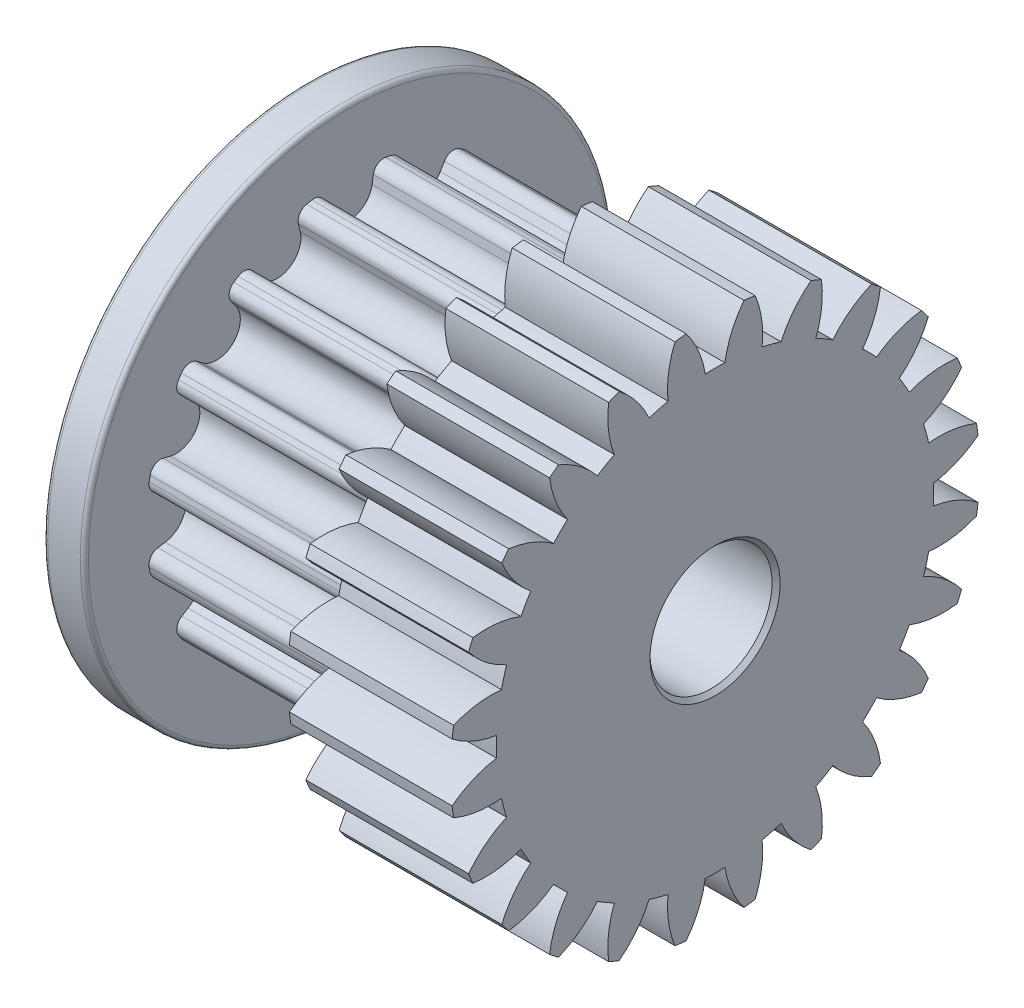
SolidWorks part; units mm, degrees
ref_plane "前视基准面" through (0, 0, 0) normal (0, 0, 1) x (1, 0, 0)
ref_plane "上视基准面" through (0, 0, 0) normal (0, 1, 0) x (1, 0, 0)
ref_plane "右视基准面" through (0, 0, 0) normal (1, 0, 0) x (0, 0, -1)
ref_plane "基准面4" through (0, 0, 0) normal (-1, 0, 0) x (0, -1, 0)
sketch "草图1" plane through (0, 0, 0) normal (-1, 0, 0) x (0, -1, 0)
  arc A0 (-0.7113, 6.461) -> (-0.9851, 6.4249) centre (0, 0) ccw
  arc A1 (-0.9851, 6.4249) -> (-1.1561, 5.2482) centre (1.2304, 5.5023) ccw
  arc A2 (-1.1561, 5.2482) -> (-1.6229, 5.1231) centre (0, 0) ccw
  arc A3 (-1.6229, 5.1231) -> (-2.3593, 6.0567) centre (-3.8167, 4.1499) ccw
  arc A4 (-2.3593, 6.0567) -> (-2.6144, 5.951) centre (0, 0) ccw
  arc A5 (-2.6144, 5.951) -> (-2.475, 4.7701) centre (-0.2356, 5.6332) ccw
  arc A6 (-2.475, 4.7701) -> (-2.8936, 4.5285) centre (0, 0) ccw
  arc A7 (-2.8936, 4.5285) -> (-3.8465, 5.2397) centre (-4.7607, 3.0206) ccw
  arc A8 (-3.8465, 5.2397) -> (-4.0656, 5.0716) centre (0, 0) ccw
  arc A9 (-4.0656, 5.0716) -> (-3.6253, 3.967) centre (-1.6855, 5.3803) ccw
  arc A10 (-3.6253, 3.967) -> (-3.967, 3.6253) centre (0, 0) ccw
  arc A11 (-3.967, 3.6253) -> (-5.0716, 4.0656) centre (-5.3803, 1.6855) ccw
  arc A12 (-5.0716, 4.0656) -> (-5.2397, 3.8465) centre (0, 0) ccw
  arc A13 (-5.2397, 3.8465) -> (-4.5285, 2.8936) centre (-3.0206, 4.7607) ccw
  arc A14 (-4.5285, 2.8936) -> (-4.7701, 2.475) centre (0, 0) ccw
  arc A15 (-4.7701, 2.475) -> (-5.951, 2.6144) centre (-5.6332, 0.2356) ccw
  arc A16 (-5.951, 2.6144) -> (-6.0567, 2.3593) centre (0, 0) ccw
  arc A17 (-6.0567, 2.3593) -> (-5.1231, 1.6229) centre (-4.1499, 3.8167) ccw
  arc A18 (-5.1231, 1.6229) -> (-5.2482, 1.1561) centre (0, 0) ccw
  arc A19 (-5.2482, 1.1561) -> (-6.4249, 0.9851) centre (-5.5023, -1.2304) ccw
  arc A20 (-6.4249, 0.9851) -> (-6.461, 0.7113) centre (0, 0) ccw
  arc A21 (-6.461, 0.7113) -> (-5.3686, 0.2416) centre (-4.9963, 2.6126) ccw
  arc A22 (-5.3686, 0.2416) -> (-5.3686, -0.2416) centre (0, 0) ccw
  arc A23 (-5.3686, -0.2416) -> (-6.461, -0.7113) centre (-4.9963, -2.6126) ccw
  arc A24 (-6.461, -0.7113) -> (-6.4249, -0.9851) centre (0, 0) ccw
  arc A25 (-6.4249, -0.9851) -> (-5.2482, -1.1561) centre (-5.5023, 1.2304) ccw
  arc A26 (-5.2482, -1.1561) -> (-5.1231, -1.6229) centre (0, 0) ccw
  arc A27 (-5.1231, -1.6229) -> (-6.0567, -2.3593) centre (-4.1499, -3.8167) ccw
  arc A28 (-6.0567, -2.3593) -> (-5.951, -2.6144) centre (0, 0) ccw
  arc A29 (-5.951, -2.6144) -> (-4.7701, -2.475) centre (-5.6332, -0.2356) ccw
  arc A30 (-4.7701, -2.475) -> (-4.5285, -2.8936) centre (0, 0) ccw
  arc A31 (-4.5285, -2.8936) -> (-5.2397, -3.8465) centre (-3.0206, -4.7607) ccw
  arc A32 (-5.2397, -3.8465) -> (-5.0716, -4.0656) centre (0, 0) ccw
  arc A33 (-5.0716, -4.0656) -> (-3.967, -3.6253) centre (-5.3803, -1.6855) ccw
  arc A34 (-3.967, -3.6253) -> (-3.6253, -3.967) centre (0, 0) ccw
  arc A35 (-3.6253, -3.967) -> (-4.0656, -5.0716) centre (-1.6855, -5.3803) ccw
  arc A36 (-4.0656, -5.0716) -> (-3.8465, -5.2397) centre (0, 0) ccw
  arc A37 (-3.8465, -5.2397) -> (-2.8936, -4.5285) centre (-4.7607, -3.0206) ccw
  arc A38 (-2.8936, -4.5285) -> (-2.475, -4.7701) centre (0, 0) ccw
  arc A39 (-2.475, -4.7701) -> (-2.6144, -5.951) centre (-0.2356, -5.6332) ccw
  arc A40 (-2.6144, -5.951) -> (-2.3593, -6.0567) centre (0, 0) ccw
  arc A41 (-2.3593, -6.0567) -> (-1.6229, -5.1231) centre (-3.8167, -4.1499) ccw
  arc A42 (-1.6229, -5.1231) -> (-1.1561, -5.2482) centre (0, 0) ccw
  arc A43 (-1.1561, -5.2482) -> (-0.9851, -6.4249) centre (1.2304, -5.5023) ccw
  arc A44 (-0.9851, -6.4249) -> (-0.7113, -6.461) centre (0, 0) ccw
  arc A45 (-0.7113, -6.461) -> (-0.2416, -5.3686) centre (-2.6126, -4.9963) ccw
  arc A46 (-0.2416, -5.3686) -> (0.2416, -5.3686) centre (0, 0) ccw
  arc A47 (0.2416, -5.3686) -> (0.7113, -6.461) centre (2.6126, -4.9963) ccw
  arc A48 (0.7113, -6.461) -> (0.9851, -6.4249) centre (0, 0) ccw
  arc A49 (0.9851, -6.4249) -> (1.1561, -5.2482) centre (-1.2304, -5.5023) ccw
  arc A50 (1.1561, -5.2482) -> (1.6229, -5.1231) centre (0, 0) ccw
  arc A51 (1.6229, -5.1231) -> (2.3593, -6.0567) centre (3.8167, -4.1499) ccw
  arc A52 (2.3593, -6.0567) -> (2.6144, -5.951) centre (0, 0) ccw
  arc A53 (2.6144, -5.951) -> (2.475, -4.7701) centre (0.2356, -5.6332) ccw
  arc A54 (2.475, -4.7701) -> (2.8936, -4.5285) centre (0, 0) ccw
  arc A55 (2.8936, -4.5285) -> (3.8465, -5.2397) centre (4.7607, -3.0206) ccw
  arc A56 (3.8465, -5.2397) -> (4.0656, -5.0716) centre (0, 0) ccw
  arc A57 (4.0656, -5.0716) -> (3.6253, -3.967) centre (1.6855, -5.3803) ccw
  arc A58 (3.6253, -3.967) -> (3.967, -3.6253) centre (0, 0) ccw
  arc A59 (3.967, -3.6253) -> (5.0716, -4.0656) centre (5.3803, -1.6855) ccw
  arc A60 (5.0716, -4.0656) -> (5.2397, -3.8465) centre (0, 0) ccw
  arc A61 (5.2397, -3.8465) -> (4.5285, -2.8936) centre (3.0206, -4.7607) ccw
  arc A62 (4.5285, -2.8936) -> (4.7701, -2.475) centre (0, 0) ccw
  arc A63 (4.7701, -2.475) -> (5.951, -2.6144) centre (5.6332, -0.2356) ccw
  arc A64 (5.951, -2.6144) -> (6.0567, -2.3593) centre (0, 0) ccw
  arc A65 (6.0567, -2.3593) -> (5.1231, -1.6229) centre (4.1499, -3.8167) ccw
  arc A66 (5.1231, -1.6229) -> (5.2482, -1.1561) centre (0, 0) ccw
  arc A67 (5.2482, -1.1561) -> (6.4249, -0.9851) centre (5.5023, 1.2304) ccw
  arc A68 (6.4249, -0.9851) -> (6.461, -0.7113) centre (0, 0) ccw
  arc A69 (6.461, -0.7113) -> (5.3686, -0.2416) centre (4.9963, -2.6126) ccw
  arc A70 (5.3686, -0.2416) -> (5.3686, 0.2416) centre (0, 0) ccw
  arc A71 (5.3686, 0.2416) -> (6.461, 0.7113) centre (4.9963, 2.6126) ccw
  arc A72 (6.461, 0.7113) -> (6.4249, 0.9851) centre (0, 0) ccw
  arc A73 (6.4249, 0.9851) -> (5.2482, 1.1561) centre (5.5023, -1.2304) ccw
  arc A74 (5.2482, 1.1561) -> (5.1231, 1.6229) centre (0, 0) ccw
  arc A75 (5.1231, 1.6229) -> (6.0567, 2.3593) centre (4.1499, 3.8167) ccw
  arc A76 (6.0567, 2.3593) -> (5.951, 2.6144) centre (0, 0) ccw
  arc A77 (5.951, 2.6144) -> (4.7701, 2.475) centre (5.6332, 0.2356) ccw
  arc A78 (4.7701, 2.475) -> (4.5285, 2.8936) centre (0, 0) ccw
  arc A79 (4.5285, 2.8936) -> (5.2397, 3.8465) centre (3.0206, 4.7607) ccw
  arc A80 (5.2397, 3.8465) -> (5.0716, 4.0656) centre (0, 0) ccw
  arc A81 (5.0716, 4.0656) -> (3.967, 3.6253) centre (5.3803, 1.6855) ccw
  arc A82 (3.967, 3.6253) -> (3.6253, 3.967) centre (0, 0) ccw
  arc A83 (3.6253, 3.967) -> (4.0656, 5.0716) centre (1.6855, 5.3803) ccw
  arc A84 (4.0656, 5.0716) -> (3.8465, 5.2397) centre (0, 0) ccw
  arc A85 (3.8465, 5.2397) -> (2.8936, 4.5285) centre (4.7607, 3.0206) ccw
  arc A86 (2.8936, 4.5285) -> (2.475, 4.7701) centre (0, 0) ccw
  arc A87 (2.475, 4.7701) -> (2.6144, 5.951) centre (0.2356, 5.6332) ccw
  arc A88 (2.6144, 5.951) -> (2.3593, 6.0567) centre (0, 0) ccw
  arc A89 (2.3593, 6.0567) -> (1.6229, 5.1231) centre (3.8167, 4.1499) ccw
  arc A90 (1.6229, 5.1231) -> (1.1561, 5.2482) centre (0, 0) ccw
  arc A91 (1.1561, 5.2482) -> (0.9851, 6.4249) centre (-1.2304, 5.5023) ccw
  arc A92 (0.9851, 6.4249) -> (0.7113, 6.461) centre (0, 0) ccw
  arc A93 (0.7113, 6.461) -> (0.2416, 5.3686) centre (2.6126, 4.9963) ccw
  arc A94 (0.2416, 5.3686) -> (-0.2416, 5.3686) centre (0, 0) ccw
  arc A95 (-0.2416, 5.3686) -> (-0.7113, 6.461) centre (-2.6126, 4.9963) ccw
  circle A96 centre (0, 0) radius 1.5
extrude "凸台-拉伸1" add sketch "草图1" against normal blind 4
sketch "草图2" plane through (0, 0, 0) normal (-1, 0, 0) x (0, 0, 1)
  line L0 (0, 5.5357) -> (0, 0) construction
  line L1 (0, 0) -> (0.994, 4.9971) construction
  line L2 (-0.8955, 4.5018) -> (0, 0) construction
  line L3 (0.9735, 4.8941) -> (1.0374, 4.8814)
  line L4 (2.3511, 4.1035) -> (2.2586, 3.9502)
  line L5 (2.7723, 4.149) -> (2.7181, 4.1852)
  line L6 (1.2391, 4.5641) -> (1.1909, 4.3689)
  line L7 (2.7723, 4.149) -> (2.8264, 4.1128)
  line L8 (3.7425, 2.8914) -> (3.5984, 2.7852)
  line L9 (4.149, 2.7723) -> (4.1128, 2.8264)
  line L10 (2.8914, 3.7425) -> (2.7722, 3.5806)
  line L11 (4.149, 2.7723) -> (4.1852, 2.7181)
  line L12 (4.5641, 1.2391) -> (4.3903, 1.1962)
  line L13 (4.8941, 0.9735) -> (4.8814, 1.0374)
  line L14 (4.1035, 2.3511) -> (3.9314, 2.2472)
  line L15 (4.8941, 0.9735) -> (4.9068, 0.9096)
  line L16 (4.6908, -0.6018) -> (4.5139, -0.575)
  line L17 (4.8941, -0.9735) -> (4.9068, -0.9096)
  line L18 (4.6908, 0.6018) -> (4.4921, 0.5717)
  line L19 (0.994, 4.9971) -> (1.3866, 6.9711) construction
  line L20 (-0.8955, 4.5018) -> (-1.4, 7.038) construction
  line L21 (-0.9735, 4.8941) -> (-0.9096, 4.9068)
  line L22 (0.6018, 4.6908) -> (0.575, 4.5139)
  line L23 (0.9735, 4.8941) -> (0.9096, 4.9068)
  line L24 (-0.6018, 4.6908) -> (-0.5717, 4.4921)
  line L25 (4.8941, -0.9735) -> (4.8814, -1.0374)
  line L26 (4.1035, -2.3511) -> (3.9502, -2.2586)
  line L27 (4.149, -2.7723) -> (4.1852, -2.7181)
  line L28 (4.5641, -1.2391) -> (4.3689, -1.1909)
  line L29 (4.149, -2.7723) -> (4.1128, -2.8264)
  line L30 (2.8914, -3.7425) -> (2.7852, -3.5984)
  line L31 (2.7723, -4.149) -> (2.8264, -4.1128)
  line L32 (3.7425, -2.8914) -> (3.5806, -2.7722)
  line L33 (2.7723, -4.149) -> (2.7181, -4.1852)
  line L34 (1.2391, -4.5641) -> (1.1962, -4.3903)
  line L35 (0.9735, -4.8941) -> (1.0374, -4.8814)
  line L36 (2.3511, -4.1035) -> (2.2472, -3.9314)
  line L37 (0.9735, -4.8941) -> (0.9096, -4.9068)
  line L38 (-0.6018, -4.6908) -> (-0.575, -4.5139)
  line L39 (-0.9735, -4.8941) -> (-0.9096, -4.9068)
  line L40 (0.6018, -4.6908) -> (0.5717, -4.4921)
  line L41 (-0.9735, -4.8941) -> (-1.0374, -4.8814)
  line L42 (-2.3511, -4.1035) -> (-2.2586, -3.9502)
  line L43 (-2.7723, -4.149) -> (-2.7181, -4.1852)
  line L44 (-1.2391, -4.5641) -> (-1.1909, -4.3689)
  line L45 (-2.7723, -4.149) -> (-2.8264, -4.1128)
  line L46 (-3.7425, -2.8914) -> (-3.5984, -2.7852)
  line L47 (-4.149, -2.7723) -> (-4.1128, -2.8264)
  line L48 (-2.8914, -3.7425) -> (-2.7722, -3.5806)
  line L49 (-4.149, -2.7723) -> (-4.1852, -2.7181)
  line L50 (-4.5641, -1.2391) -> (-4.3903, -1.1962)
  line L51 (-4.8941, -0.9735) -> (-4.8814, -1.0374)
  line L52 (-4.1035, -2.3511) -> (-3.9314, -2.2472)
  line L53 (-4.8941, -0.9735) -> (-4.9068, -0.9096)
  line L54 (-4.6908, 0.6018) -> (-4.5139, 0.575)
  line L55 (-4.8941, 0.9735) -> (-4.9068, 0.9096)
  line L56 (-4.6908, -0.6018) -> (-4.4921, -0.5717)
  line L57 (-4.8941, 0.9735) -> (-4.8814, 1.0374)
  line L58 (-4.1035, 2.3511) -> (-3.9502, 2.2586)
  line L59 (-4.149, 2.7723) -> (-4.1852, 2.7181)
  line L60 (-4.5641, 1.2391) -> (-4.3689, 1.1909)
  line L61 (-4.149, 2.7723) -> (-4.1128, 2.8264)
  line L62 (-2.8914, 3.7425) -> (-2.7852, 3.5984)
  line L63 (-2.7723, 4.149) -> (-2.8264, 4.1128)
  line L64 (-3.7425, 2.8914) -> (-3.5806, 2.7722)
  line L65 (-2.7723, 4.149) -> (-2.7181, 4.1852)
  line L66 (-1.2391, 4.5641) -> (-1.1962, 4.3903)
  line L67 (-0.9735, 4.8941) -> (-1.0374, 4.8814)
  line L68 (-2.3511, 4.1035) -> (-2.2472, 3.9314)
  circle A0 centre (0, 0) radius 4.99 construction
  circle A1 centre (0, 0) radius 4.59 construction
  arc A2 (-0.5717, 4.4921) -> (0.575, 4.5139) centre (0, 4.59) ccw
  arc A3 (-0.6018, 4.6908) -> (-0.9096, 4.9068) centre (-0.8589, 4.6518) ccw
  arc A4 (0.6018, 4.6908) -> (0.9096, 4.9068) centre (0.8589, 4.6518) cw
  arc A5 (1.1909, 4.3689) -> (2.2586, 3.9502) centre (1.7565, 4.2406) ccw
  arc A6 (1.2391, 4.5641) -> (1.0374, 4.8814) centre (0.9867, 4.6264) ccw
  arc A7 (2.3511, 4.1035) -> (2.7181, 4.1852) centre (2.5737, 3.969) cw
  arc A8 (2.7722, 3.5806) -> (3.5984, 2.7852) centre (3.2456, 3.2456) ccw
  arc A9 (2.8914, 3.7425) -> (2.8264, 4.1128) centre (2.682, 3.8967) ccw
  arc A10 (3.7425, 2.8914) -> (4.1128, 2.8264) centre (3.8967, 2.682) cw
  arc A11 (3.9314, 2.2472) -> (4.3903, 1.1962) centre (4.2406, 1.7565) ccw
  arc A12 (4.1035, 2.3511) -> (4.1852, 2.7181) centre (3.969, 2.5737) ccw
  arc A13 (4.5641, 1.2391) -> (4.8814, 1.0374) centre (4.6264, 0.9867) cw
  arc A14 (4.4921, 0.5717) -> (4.5139, -0.575) centre (4.59, 0) ccw
  arc A15 (4.6908, 0.6018) -> (4.9068, 0.9096) centre (4.6518, 0.8589) ccw
  arc A16 (4.6908, -0.6018) -> (4.9068, -0.9096) centre (4.6518, -0.8589) cw
  arc A17 (4.3689, -1.1909) -> (3.9502, -2.2586) centre (4.2406, -1.7565) ccw
  arc A18 (4.5641, -1.2391) -> (4.8814, -1.0374) centre (4.6264, -0.9867) ccw
  arc A19 (4.1035, -2.3511) -> (4.1852, -2.7181) centre (3.969, -2.5737) cw
  arc A20 (3.5806, -2.7722) -> (2.7852, -3.5984) centre (3.2456, -3.2456) ccw
  arc A21 (3.7425, -2.8914) -> (4.1128, -2.8264) centre (3.8967, -2.682) ccw
  arc A22 (2.8914, -3.7425) -> (2.8264, -4.1128) centre (2.682, -3.8967) cw
  arc A23 (2.2472, -3.9314) -> (1.1962, -4.3903) centre (1.7565, -4.2406) ccw
  arc A24 (2.3511, -4.1035) -> (2.7181, -4.1852) centre (2.5737, -3.969) ccw
  arc A25 (1.2391, -4.5641) -> (1.0374, -4.8814) centre (0.9867, -4.6264) cw
  arc A26 (0.5717, -4.4921) -> (-0.575, -4.5139) centre (0, -4.59) ccw
  arc A27 (0.6018, -4.6908) -> (0.9096, -4.9068) centre (0.8589, -4.6518) ccw
  arc A28 (-0.6018, -4.6908) -> (-0.9096, -4.9068) centre (-0.8589, -4.6518) cw
  arc A29 (-1.1909, -4.3689) -> (-2.2586, -3.9502) centre (-1.7565, -4.2406) ccw
  arc A30 (-1.2391, -4.5641) -> (-1.0374, -4.8814) centre (-0.9867, -4.6264) ccw
  arc A31 (-2.3511, -4.1035) -> (-2.7181, -4.1852) centre (-2.5737, -3.969) cw
  arc A32 (-2.7722, -3.5806) -> (-3.5984, -2.7852) centre (-3.2456, -3.2456) ccw
  arc A33 (-2.8914, -3.7425) -> (-2.8264, -4.1128) centre (-2.682, -3.8967) ccw
  arc A34 (-3.7425, -2.8914) -> (-4.1128, -2.8264) centre (-3.8967, -2.682) cw
  arc A35 (-3.9314, -2.2472) -> (-4.3903, -1.1962) centre (-4.2406, -1.7565) ccw
  arc A36 (-4.1035, -2.3511) -> (-4.1852, -2.7181) centre (-3.969, -2.5737) ccw
  arc A37 (-4.5641, -1.2391) -> (-4.8814, -1.0374) centre (-4.6264, -0.9867) cw
  arc A38 (-4.4921, -0.5717) -> (-4.5139, 0.575) centre (-4.59, 0) ccw
  arc A39 (-4.6908, -0.6018) -> (-4.9068, -0.9096) centre (-4.6518, -0.8589) ccw
  arc A40 (-4.6908, 0.6018) -> (-4.9068, 0.9096) centre (-4.6518, 0.8589) cw
  arc A41 (-4.3689, 1.1909) -> (-3.9502, 2.2586) centre (-4.2406, 1.7565) ccw
  arc A42 (-4.5641, 1.2391) -> (-4.8814, 1.0374) centre (-4.6264, 0.9867) ccw
  arc A43 (-4.1035, 2.3511) -> (-4.1852, 2.7181) centre (-3.969, 2.5737) cw
  arc A44 (-3.5806, 2.7722) -> (-2.7852, 3.5984) centre (-3.2456, 3.2456) ccw
  arc A45 (-3.7425, 2.8914) -> (-4.1128, 2.8264) centre (-3.8967, 2.682) ccw
  arc A46 (-2.8914, 3.7425) -> (-2.8264, 4.1128) centre (-2.682, 3.8967) cw
  arc A47 (-2.2472, 3.9314) -> (-1.1962, 4.3903) centre (-1.7565, 4.2406) ccw
  arc A48 (-2.3511, 4.1035) -> (-2.7181, 4.1852) centre (-2.5737, 3.969) ccw
  arc A49 (-1.2391, 4.5641) -> (-1.0374, 4.8814) centre (-0.9867, 4.6264) cw
  point P188 (0, 0)
  dimension "D1" = 9.18
  dimension "D2" = 1.16
  dimension "D4" = 0.52
  dimension "D3" = 16
  dimension "D5" = 0.4
extrude "凸台-拉伸2" add sketch "草图2" along normal blind 5
sketch "草图3" plane through (-5, 0, 0) normal (-1, 0, 0) x (0, 0, 1)
  circle A0 centre (0, 0) radius 6.5
  dimension "D1" = 13
extrude "凸台-拉伸3" add sketch "草图3" along normal blind 1
sketch "草图5" plane through (4, 0, 0) normal (1, 0, 0) x (0, 0, -1)
  circle A0 centre (0, 0) radius 1.5
extrude "切除-拉伸1" cut sketch "草图5" against normal through all
chamfer "倒角1" distance 0.1 angle 45 2 edges at (4, 0, 1.5) (-6, 0, -1.5)
fillet "圆角1" radius 0.1 2 edges at (-5, 0, 6.5) (-6, 0, 6.5)
